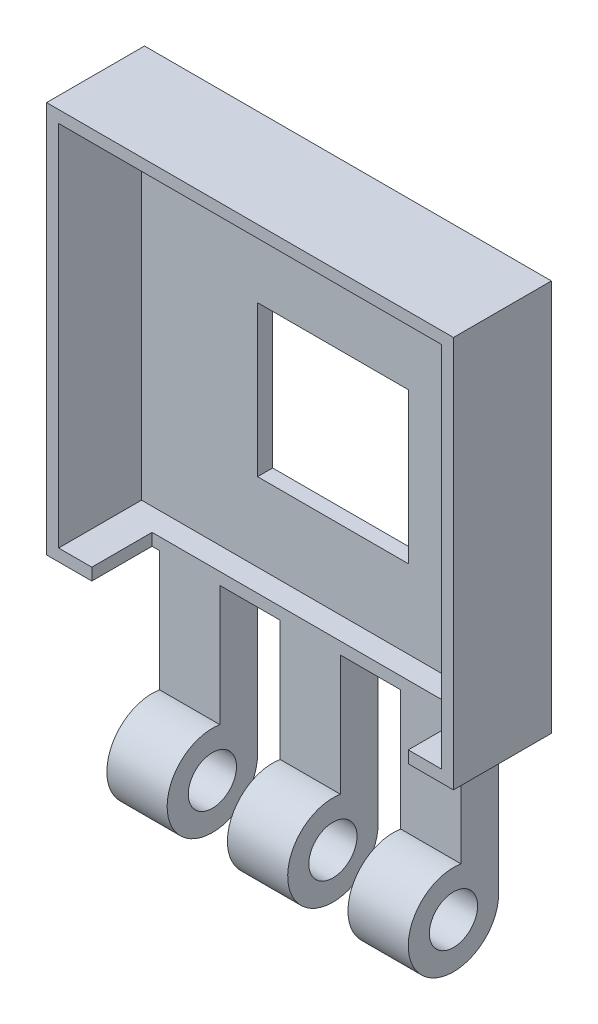
SolidWorks part; units mm, degrees
ref_plane "Plan de face" through (0, 0, 0) normal (0, 0, 1) x (1, 0, 0)
ref_plane "Plan de dessus" through (0, 0, 0) normal (0, 1, 0) x (1, 0, 0)
ref_plane "Plan de droite" through (0, 0, 0) normal (1, 0, 0) x (0, 0, -1)
sketch "Esquisse1" plane through (0, 0, 0) normal (0, 0, 1) x (1, 0, 0)
  line L0 (0, 26) -> (0, 0) construction
  line L1 (-13.5, 0) -> (13.5, 0)
  line L2 (-13.5, 0) -> (-13.5, 26)
  line L3 (-13.5, 26) -> (13.5, 26)
  line L4 (13.5, 0) -> (13.5, 26)
  line L5 (-5, 16) -> (5, 16)
  line L6 (-5, 16) -> (-5, 6)
  line L7 (-5, 6) -> (5, 6)
  line L8 (5, 16) -> (5, 6)
  point P4 (0, 0)
  point P11 (0, 16)
  point P12 (0, 0)
  point P13 (0, 0)
  dimension "D1" = 26
  dimension "D2" = 27
  dimension "D3" = 10
  dimension "D4" = 10
  dimension "D5" = 16
extrude "Boss.-Extru.1" add sketch "Esquisse1" along normal blind 1
sketch "Esquisse2" plane through (0, 0, 1) normal (0, 0, 1) x (1, 0, 0)
  line L0 (-12.7, 25.2) -> (-12.7, 0.8)
  line L1 (-13.5, 26) -> (13.5, 26)
  line L2 (-13.5, 26) -> (-13.5, 0)
  line L3 (-13.5, 0) -> (13.5, 0)
  line L4 (13.5, 26) -> (13.5, 0)
  line L5 (-12.7, 0.8) -> (12.7, 0.8)
  line L6 (12.7, 25.2) -> (12.7, 0.8)
  line L7 (-12.7, 25.2) -> (12.7, 25.2)
  dimension "D1" = 0.8
extrude "Boss.-Extru.2" add sketch "Esquisse2" along normal blind 5.5
sketch "Esquisse3" plane through (0, 0, 0) normal (0, -1, 0) x (1, 0, 0)
  line L0 (0, 6.5) -> (0, 0) construction
  line L1 (-10.5, 6.5) -> (10.5, 6.5)
  line L2 (-10.5, 6.5) -> (-10.5, 2.5)
  line L3 (-10.5, 2.5) -> (10.5, 2.5)
  line L4 (10.5, 6.5) -> (10.5, 2.5)
  line L5 (-13.5, 6.5) -> (13.5, 6.5) construction
  line L6 (-13.5, 0) -> (13.5, 0) construction
  point P10 (0, 6.5)
  dimension "D1" = 21
  dimension "D2" = 2.5
extrude "Enlèv. mat.-Extru.1" cut sketch "Esquisse3" against normal up to next
sketch "Esquisse4" plane through (0, 0, 0) normal (1, 0, 0) x (0, 0, -1)
  line L0 (0, -8) -> (0, -10.958)
  line L1 (-2.5, 0) -> (0, 0)
  line L2 (-2.5, 0) -> (-2.5, -8)
  line L3 (-2.5, -8) -> (0, -8) construction
  line L4 (0, 0) -> (0, -8)
  circle A0 centre (-3, -10.958) radius 3 construction
  arc A1 (-2.5, -8) -> (0, -10.958) centre (-3, -10.958) ccw
  circle A2 centre (-3, -10.958) radius 1.6
  dimension "D1" = 8
  dimension "D2" = 3.2
  dimension "D3" = 6
extrude "Boss.-Extru.3" add sketch "Esquisse4" along normal blind 2 and the other way blind 2
sketch "Esquisse5" plane through (0, 0, 0) normal (0, -1, 0) x (1, 0, 0)
  line L0 (-10.5, 2.5) -> (-2, 2.5) construction
  line L1 (-10, 2.5) -> (10, 2.5)
  line L2 (-10, 2.5) -> (-10, 0)
  line L3 (-10, 0) -> (10, 0)
  line L4 (10, 2.5) -> (10, 0)
  line L5 (2, 0) -> (13.5, 0) construction
  line L6 (0, 0) -> (0, 2.5) construction
  point P11 (0, 0)
  point P12 (0, 2.5)
  dimension "D1" = 20
pattern_linear "Répétition linéaire1" count 2 spacing 8 along (-1, 0, 0) count 2 spacing 8 along (1, 0, 0) of "Boss.-Extru.3"
